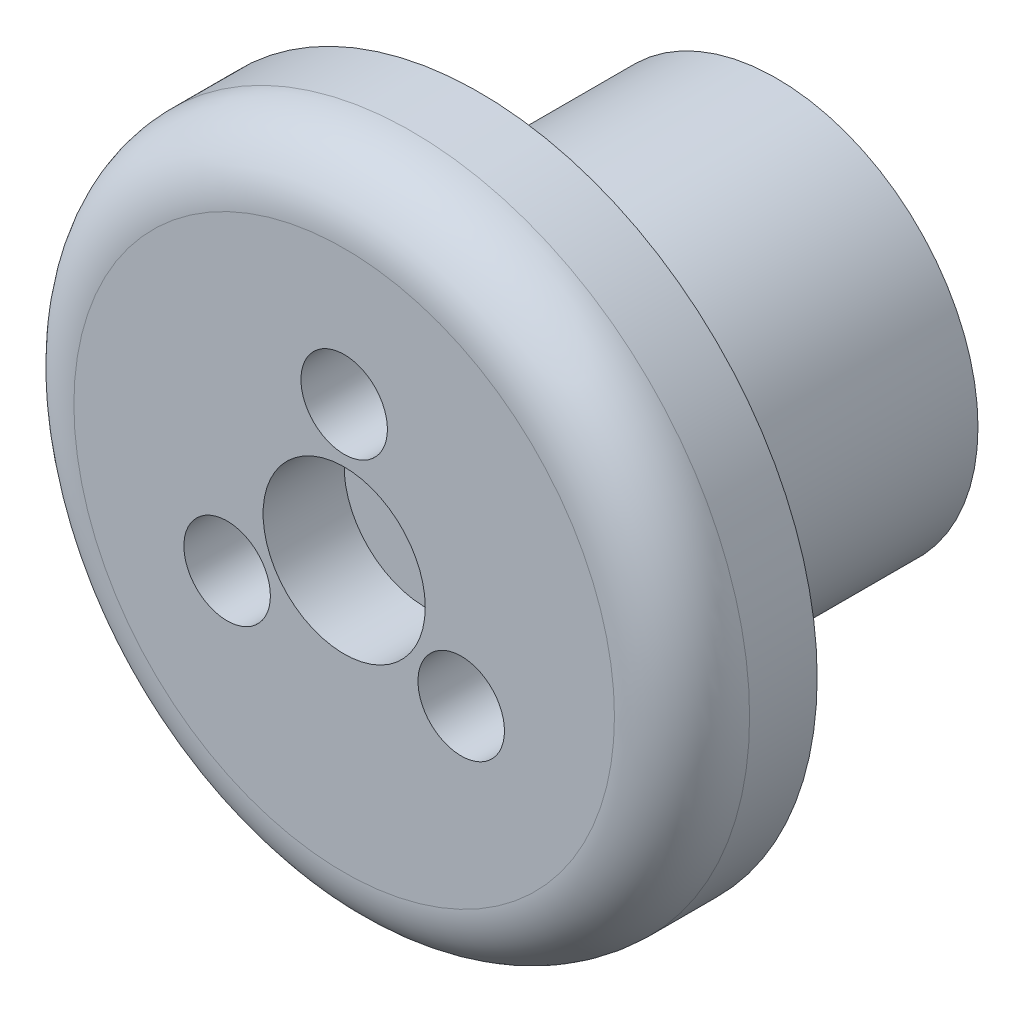
SolidWorks part; units mm, degrees
ref_plane "Front Plane" through (0, 0, 0) normal (0, 0, 1) x (1, 0, 0)
ref_plane "Top Plane" through (0, 0, 0) normal (0, 1, 0) x (1, 0, 0)
ref_plane "Right Plane" through (0, 0, 0) normal (1, 0, 0) x (0, 0, -1)
sketch "Sketch2" plane through (0, 0, 0) normal (0, 0, 1) x (1, 0, 0)
  circle A0 centre (0, 0) radius 7.45
  dimension "D1" = 14.9
extrude "Boss-Extrude1" add sketch "Sketch2" along normal blind 11
sketch "Sketch3" plane through (0, 0, 11) normal (0, 0, 1) x (1, 0, 0)
  circle A0 centre (0, 0) radius 12.5
  dimension "D1" = 25
extrude "Boss-Extrude2" add sketch "Sketch3" along normal blind 5
sketch "Sketch4" plane through (0, 0, 16) normal (0, 0, 1) x (1, 0, 0)
  line L0 (0, 0) -> (0, 5) construction
  circle A0 centre (0, 5) radius 1.6
  circle A1 centre (4.3301, -2.5) radius 1.6
  circle A2 centre (-4.3301, -2.5) radius 1.6
  point P10 (0, 0)
  dimension "D1" = 5
  dimension "D2" = 3.2
  dimension "D3" = 3
extrude "Cut-Extrude1" cut sketch "Sketch4" against normal through all
fillet "Fillet2" radius 2.5 1 edges at (12.5, 0, 16)
sketch "Sketch5" plane through (0, 0, 16) normal (0, 0, 1) x (1, 0, 0)
  circle A0 centre (0, 0) radius 3
  dimension "D1" = 6
extrude "Cut-Extrude2" cut sketch "Sketch5" against normal blind 3
